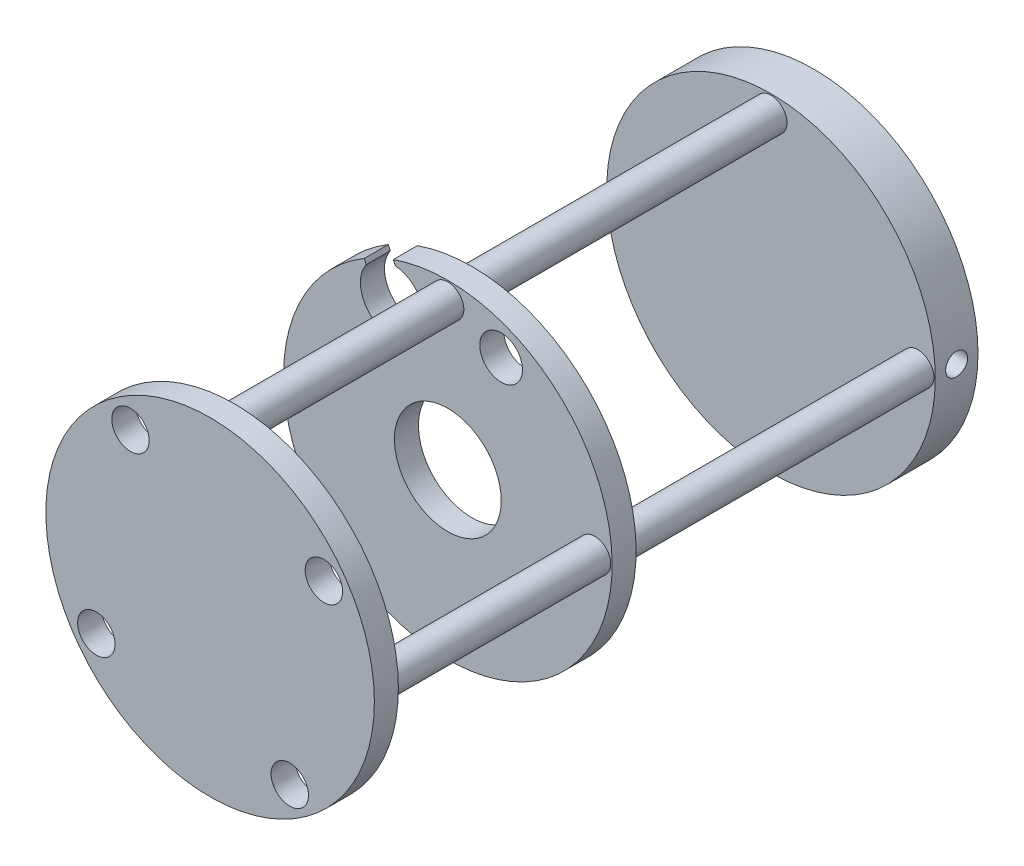
SolidWorks part; units mm, degrees
ref_plane "Plan de face" through (0, 0, 0) normal (0, 0, 1) x (1, 0, 0)
ref_plane "Plan de dessus" through (0, 0, 0) normal (0, 1, 0) x (1, 0, 0)
ref_plane "Plan de droite" through (0, 0, 0) normal (1, 0, 0) x (0, 0, -1)
sketch "Esquisse1" plane through (0, 0, 0) normal (0, 0, 1) x (1, 0, 0)
  circle A0 centre (0, 0) radius 30.75
  dimension "D1" = 61.5
extrude "Boss.-Extru.1" add sketch "Esquisse1" along normal blind 8
sketch "Esquisse2" plane through (0, 0, 8) normal (0, 0, 1) x (1, 0, 0)
  line L0 (-27.5, 0) -> (0, 0) construction
  line L1 (0, 0) -> (0, 27.5) construction
  line L2 (0, 0) -> (0, -27.5) construction
  circle A0 centre (0, 0) radius 27.5 construction
  circle A1 centre (0, 27.5) radius 3
  circle A2 centre (27.5, 0) radius 3
  circle A3 centre (-27.5, 0) radius 3
  circle A4 centre (0, -27.5) radius 3
  dimension "D2" = 55
  dimension "D3" = 6
  dimension "D1" = 90
extrude "Boss.-Extru.2" add sketch "Esquisse2" along normal blind 56
sketch "Esquisse4" plane through (0, 0, 64) normal (0, 0, 1) x (1, 0, 0)
  circle A0 centre (0, 0) radius 30.75
  dimension "D1" = 61.5
extrude "Boss.-Extru.4" add sketch "Esquisse4" along normal blind 4.5
sketch "Esquisse6" plane through (0, 0, 68.5) normal (0, 0, 1) x (1, 0, 0)
  circle A7 centre (0, -27.5) radius 3 construction
  circle A8 centre (-27.5, 0) radius 3 construction
  circle A9 centre (0, 27.5) radius 3 construction
  circle A10 centre (27.5, 0) radius 3 construction
  circle A11 centre (0, -27.5) radius 3
  circle A12 centre (-27.5, 0) radius 3
  circle A13 centre (0, 27.5) radius 3
  circle A14 centre (27.5, 0) radius 3
extrude "Boss.-Extru.5" add sketch "Esquisse6" along normal blind 40
sketch "Esquisse12" plane through (0, 0, 68.5) normal (0, 0, 1) x (1, 0, 0)
  circle A0 centre (9.9869, 23.2244) radius 4
  dimension "D1" = 8
extrude "Enlèv. mat.-Extru.1" cut sketch "Esquisse12" against normal blind 6
sketch "Esquisse13" plane through (0, 0, 68.5) normal (0, 0, 1) x (1, 0, 0)
  line L0 (0, 24.5) -> (0, 0) construction
  line L1 (0, 0) -> (-10.3541, 22.2045) construction
  line L2 (-15.6524, 26.4682) -> (-15.2691, 25.646)
  line L3 (-10.2146, 29.0039) -> (-9.8312, 28.1817)
  arc A0 (-15.2691, 25.646) -> (-9.8312, 28.1817) centre (-10.3541, 22.2045) ccw
  circle A1 centre (0, 0) radius 24.5 construction
  circle A2 centre (0, 0) radius 30.75 construction
  arc A3 (-10.2146, 29.0039) -> (-15.6524, 26.4682) centre (0, 0) ccw
  dimension "D1" = 49
  dimension "D3" = 12
  dimension "D2" = 25
  dimension "D4" = 6
extrude "Enlèv. mat.-Extru.2" cut sketch "Esquisse13" against normal blind 10
sketch "Esquisse15" plane through (0, 0, 68.5) normal (0, 0, 1) x (1, 0, 0)
  circle A0 centre (0, 0) radius 10
  dimension "D1" = 20
extrude "Enlèv. mat.-Extru.3" cut sketch "Esquisse15" against normal blind 10 contours A0
sketch "Esquisse18" plane through (0, 0, 108.5) normal (0, 0, 1) x (1, 0, 0)
  circle A1 centre (0, 0) radius 30.75
  circle A2 centre (0, 0) radius 30.75
  dimension "D1" = 0
extrude "Boss.-Extru.10" add sketch "Esquisse18" along normal blind 4.5
ref_plane "Plan1" through (-30.75, 0, 0) normal (-1, 0, 0) x (0, 0, 1)
sketch "Esquisse19" plane through (-30.75, 0, 0) normal (-1, 0, 0) x (0, 0, 1)
  line L0 (0, 30.75) -> (0, -30.75) construction
  line L1 (0, -30.75) -> (8, -30.75) construction
  circle A0 centre (4, 0.25) radius 2.05
  dimension "D1" = 4.1
  dimension "D2" = 4
  dimension "D3" = 31
extrude "Enlèv. mat.-Extru.4" cut sketch "Esquisse19" against normal blind 62
sketch "Esquisse20" plane through (0, 0, 113) normal (0, 0, 1) x (1, 0, 0)
  line L0 (0, 0) -> (-14.913, 21.298) construction
  line L1 (0, 0) -> (21.298, 14.913) construction
  line L2 (0, 0) -> (0, 14.8545) construction
  circle A0 centre (0, 0) radius 30.75 construction
  circle A1 centre (21.298, 14.913) radius 3.5
  circle A2 centre (-14.913, 21.298) radius 3.5
  circle A3 centre (-21.298, -14.913) radius 3.5
  circle A4 centre (14.913, -21.298) radius 3.5
  dimension "D2" = 7
  dimension "D1" = 26
  dimension "D3" = 90
  dimension "D4" = 35
extrude "Enlèv. mat.-Extru.5" cut sketch "Esquisse20" against normal blind 10
